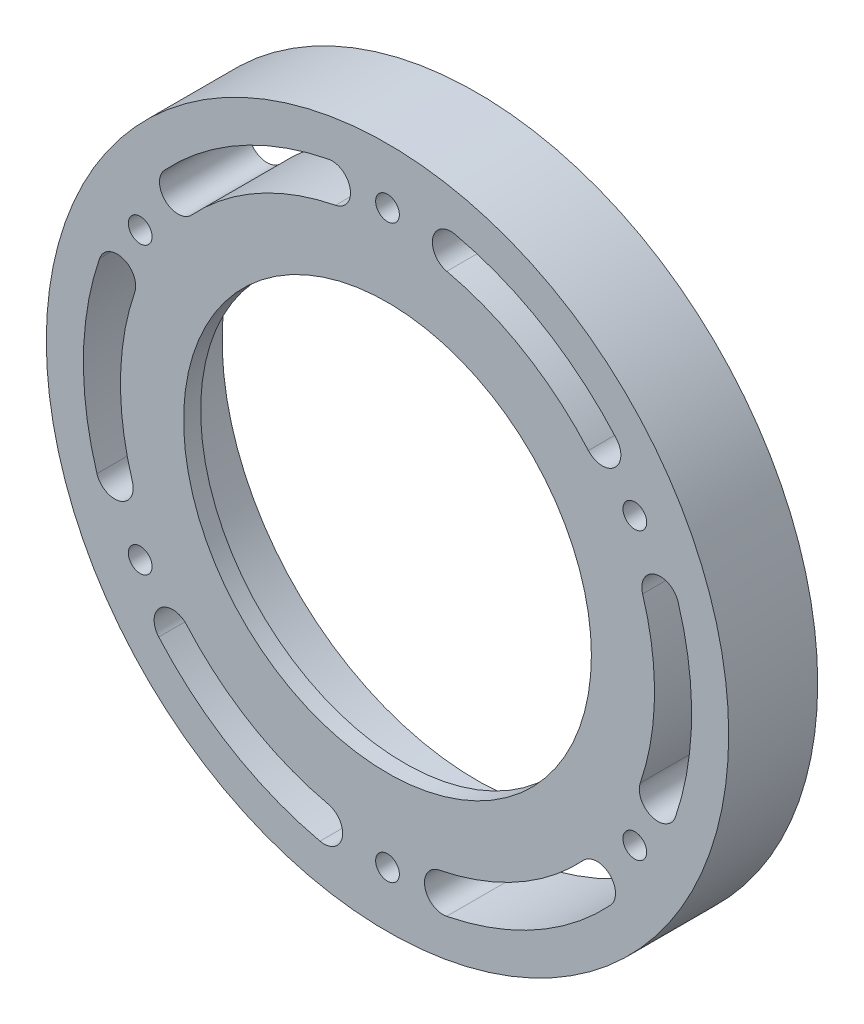
SolidWorks part; units mm, degrees
ref_plane "前视基准面" through (0, 0, 0) normal (0, 0, 1) x (1, 0, 0)
ref_plane "上视基准面" through (0, 0, 0) normal (0, 1, 0) x (1, 0, 0)
ref_plane "右视基准面" through (0, 0, 0) normal (1, 0, 0) x (0, 0, -1)
other "Configuration Table"
sketch "草图1" plane through (0, 0, 0) normal (0, 0, 1) x (1, 0, 0)
  line L0 (0, 72.4567) -> (0, -52.5061) construction
  circle A0 centre (0, 0) radius 34.3
  circle A1 centre (0, 0) radius 46
  circle A2 centre (0, 38.5) radius 1.6
  circle A3 centre (33.342, 19.25) radius 1.6
  circle A4 centre (33.342, -19.25) radius 1.6
  circle A5 centre (0, -38.5) radius 1.6
  circle A6 centre (-33.342, -19.25) radius 1.6
  circle A7 centre (-33.342, 19.25) radius 1.6
  arc A8 (-7.4886, 37.7647) -> (-28.2371, 26.1709) centre (0, 0) ccw construction
  arc A9 (-7.9749, 40.2169) -> (-30.0707, 27.8703) centre (0, 0) ccw
  arc A10 (-7.0023, 35.3124) -> (-26.4035, 24.4715) centre (0, 0) ccw
  arc A11 (-7.0023, 35.3124) -> (-7.9749, 40.2169) centre (-7.4886, 37.7647) ccw
  arc A12 (-30.0707, 27.8703) -> (-26.4035, 24.4715) centre (-28.2371, 26.1709) ccw
  arc A13 (28.9609, 25.3677) -> (8.5461, 37.5395) centre (0, 0) ccw construction
  arc A14 (30.8414, 27.0149) -> (9.1011, 39.9771) centre (0, 0) ccw
  arc A15 (27.0803, 23.7204) -> (7.9912, 35.1019) centre (0, 0) ccw
  arc A16 (27.0803, 23.7204) -> (30.8414, 27.0149) centre (28.9609, 25.3677) ccw
  arc A17 (9.1011, 39.9771) -> (7.9912, 35.1019) centre (8.5461, 37.5395) ccw
  arc A18 (36.4495, -12.397) -> (36.7832, 11.3686) centre (0, 0) ccw construction
  arc A19 (38.8163, -13.202) -> (39.1717, 12.1068) centre (0, 0) ccw
  arc A20 (34.0826, -11.592) -> (34.3947, 10.6304) centre (0, 0) ccw
  arc A21 (34.0826, -11.592) -> (38.8163, -13.202) centre (36.4495, -12.397) ccw
  arc A22 (39.1717, 12.1068) -> (34.3947, 10.6304) centre (36.7832, 11.3686) ccw
  arc A23 (7.4886, -37.7647) -> (28.2371, -26.1709) centre (0, 0) ccw construction
  arc A24 (7.9749, -40.2169) -> (30.0707, -27.8703) centre (0, 0) ccw
  arc A25 (7.0023, -35.3124) -> (26.4035, -24.4715) centre (0, 0) ccw
  arc A26 (7.0023, -35.3124) -> (7.9749, -40.2169) centre (7.4886, -37.7647) ccw
  arc A27 (30.0707, -27.8703) -> (26.4035, -24.4715) centre (28.2371, -26.1709) ccw
  arc A28 (-28.9609, -25.3677) -> (-8.5461, -37.5395) centre (0, 0) ccw construction
  arc A29 (-30.8414, -27.0149) -> (-9.1011, -39.9771) centre (0, 0) ccw
  arc A30 (-27.0803, -23.7204) -> (-7.9912, -35.1019) centre (0, 0) ccw
  arc A31 (-27.0803, -23.7204) -> (-30.8414, -27.0149) centre (-28.9609, -25.3677) ccw
  arc A32 (-9.1011, -39.9771) -> (-7.9912, -35.1019) centre (-8.5461, -37.5395) ccw
  arc A33 (-36.4495, 12.397) -> (-36.7832, -11.3686) centre (0, 0) ccw construction
  arc A34 (-38.8163, 13.202) -> (-39.1717, -12.1068) centre (0, 0) ccw
  arc A35 (-34.0826, 11.592) -> (-34.3947, -10.6304) centre (0, 0) ccw
  arc A36 (-34.0826, 11.592) -> (-38.8163, 13.202) centre (-36.4495, 12.397) ccw
  arc A37 (-39.1717, -12.1068) -> (-34.3947, -10.6304) centre (-36.7832, -11.3686) ccw
  circle A38 centre (0, 0) radius 38.5 construction
  point P10 (-18.7799, 33.609)
  point P21 (0, 0)
  point P31 (19.7163, 33.0684)
  point P38 (38.4962, -0.5406)
  point P45 (18.7799, -33.609)
  point P52 (-19.7163, -33.0684)
  point P59 (-38.4962, 0.5406)
  point P64 (0, 0)
  dimension "D1" = 92
  dimension "D2" = 68.6
  dimension "D3" = 6
  dimension "D5" = 77
  dimension "D4" = 6
extrude "凸台-拉伸1" add sketch "草图1" along normal blind 12
sketch "草图4" plane through (0, 0, 12) normal (0, 0, 1) x (1, 0, 0)
  circle A0 centre (0, 0) radius 34.3
  circle A1 centre (0, 0) radius 27.4883
extrude "凸台-拉伸2" add sketch "草图4" against normal blind 2.3
